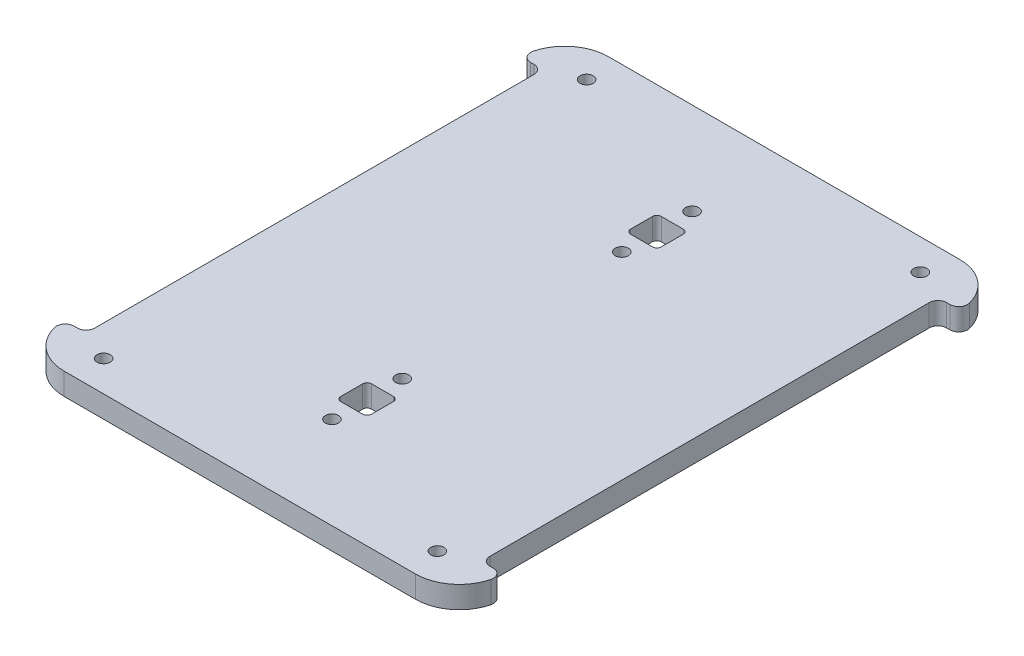
SolidWorks part; units mm, degrees
material "Acrílico (médio-alto impacto)"
ref_plane "Plano frontal" through (0, 0, 0) normal (0, 0, 1) x (1, 0, 0)
ref_plane "Plano superior" through (0, 0, 0) normal (0, 1, 0) x (1, 0, 0)
ref_plane "Plano direito" through (0, 0, 0) normal (1, 0, 0) x (0, 0, -1)
sketch "Esboço1" plane through (0, 0, 0) normal (0, 1, 0) x (1, 0, 0)
  line L0 (57.8257, 13.5994) -> (57.0797, 13.5994)
  line L1 (-29.9203, 127.5994) -> (50.0797, 127.5994)
  line L2 (57.8257, 117.5994) -> (57.0797, 117.5994)
  line L3 (-29.9203, 3.5994) -> (50.0797, 3.5994)
  line L4 (55.0797, 115.5994) -> (55.0797, 15.5994)
  line L5 (-37.6663, 117.5994) -> (-36.9203, 117.5994)
  line L6 (-37.6663, 13.5994) -> (-36.9203, 13.5994)
  line L7 (-34.9203, 115.5994) -> (-34.9203, 15.5994)
  arc A0 (59.7622, 120.0994) -> (50.0797, 127.5994) centre (50.0797, 117.5994) ccw
  arc A1 (50.0797, 3.5994) -> (59.7622, 11.0994) centre (50.0797, 13.5994) ccw
  arc A2 (-39.6028, 120.0994) -> (-29.9203, 127.5994) centre (-29.9203, 117.5994) cw
  arc A3 (-39.6028, 11.0994) -> (-29.9203, 3.5994) centre (-29.9203, 13.5994) ccw
  arc A4 (57.8257, 13.5994) -> (59.7622, 11.0994) centre (57.8257, 11.5994) cw
  arc A5 (55.0797, 15.5994) -> (57.0797, 13.5994) centre (57.0797, 15.5994) ccw
  arc A6 (57.8257, 117.5994) -> (59.7622, 120.0994) centre (57.8257, 119.5994) ccw
  arc A7 (55.0797, 115.5994) -> (57.0797, 117.5994) centre (57.0797, 115.5994) cw
  arc A8 (-36.9203, 117.5994) -> (-34.9203, 115.5994) centre (-36.9203, 115.5994) cw
  arc A9 (-37.6663, 117.5994) -> (-39.6028, 120.0994) centre (-37.6663, 119.5994) cw
  arc A10 (-36.9203, 13.5994) -> (-34.9203, 15.5994) centre (-36.9203, 15.5994) ccw
  arc A11 (-37.6663, 13.5994) -> (-39.6028, 11.0994) centre (-37.6663, 11.5994) ccw
  dimension "D1" = 10
  dimension "D2" = 2
extrude "Ressalto-extrusão1" add sketch "Esboço1" along normal blind 5
sketch "Esboço2" plane through (0, 5, 0) normal (0, 1, 0) x (1, 0, 0)
  line L0 (55.0797, 15.5994) -> (-49.7304, 15.5994) construction
  line L1 (-34.9203, 65.5994) -> (55.0797, 65.5994)
  line L2 (-34.9203, 115.5994) -> (-34.9203, 15.5994) construction
  line L3 (55.0797, 15.5994) -> (55.0797, 115.5994) construction
  line L4 (13.5797, 96.0994) -> (13.5797, 101.0994)
  line L5 (7.5797, 36.0994) -> (12.5797, 36.0994)
  line L6 (6.5797, 35.0994) -> (6.5797, 30.0994)
  line L7 (7.5797, 29.0994) -> (12.5797, 29.0994)
  line L8 (13.5797, 35.0994) -> (13.5797, 30.0994)
  line L9 (7.5797, 102.0994) -> (12.5797, 102.0994)
  line L10 (6.5797, 96.0994) -> (6.5797, 101.0994)
  line L11 (7.5797, 95.0994) -> (12.5797, 95.0994)
  circle A0 centre (10.0797, 24.5994) radius 1.5
  circle A1 centre (10.0797, 40.5994) radius 1.5
  circle A2 centre (10.0797, 90.5994) radius 1.5
  circle A3 centre (10.0797, 106.5994) radius 1.5
  arc A4 (12.5797, 36.0994) -> (13.5797, 35.0994) centre (12.5797, 35.0994) cw
  arc A5 (12.5797, 29.0994) -> (13.5797, 30.0994) centre (12.5797, 30.0994) ccw
  arc A6 (6.5797, 30.0994) -> (7.5797, 29.0994) centre (7.5797, 30.0994) ccw
  arc A7 (7.5797, 36.0994) -> (6.5797, 35.0994) centre (7.5797, 35.0994) ccw
  arc A8 (7.5797, 95.0994) -> (6.5797, 96.0994) centre (7.5797, 96.0994) cw
  arc A9 (6.5797, 101.0994) -> (7.5797, 102.0994) centre (7.5797, 101.0994) cw
  arc A10 (12.5797, 102.0994) -> (13.5797, 101.0994) centre (12.5797, 101.0994) cw
  arc A11 (12.5797, 95.0994) -> (13.5797, 96.0994) centre (12.5797, 96.0994) ccw
  dimension "D1" = 16
  dimension "D2" = 9
  dimension "D3" = 3
  dimension "D4" = 3
  dimension "D7" = 45
  dimension "D8" = 45
  dimension "D9" = 1
  dimension "D5" = 41.5
  dimension "D6" = 41.5
  dimension "D10" = 4.5
  dimension "D11" = 4.5
extrude "Corte-extrusão1" cut sketch "Esboço2" against normal blind 5 contours A1 | A0 | A2 | A3 | L6 A6 L7 A5 L8 A4 L5 A7 | L10 A9 L9 A10 L4 A11 L11 A8
sketch "Esboço3" plane through (0, 5, 0) normal (0, 1, 0) x (1, 0, 0)
  line L0 (-29.9203, 3.5994) -> (50.0797, 3.5994) construction
  line L1 (-34.9203, 115.5994) -> (-34.9203, 15.5994) construction
  line L2 (55.0797, 15.5994) -> (55.0797, 115.5994) construction
  line L3 (50.0797, 127.5994) -> (-29.9203, 127.5994) construction
  circle A0 centre (-27.9203, 10.5994) radius 1.5
  circle A1 centre (48.0797, 10.5994) radius 1.5
  circle A2 centre (-27.9203, 120.5994) radius 1.5
  circle A3 centre (48.0797, 120.5994) radius 1.5
  dimension "D1" = 7
  dimension "D2" = 7
  dimension "D3" = 7
  dimension "D4" = 7
  dimension "D5" = 7
  dimension "D6" = 7
  dimension "D7" = 7
  dimension "D8" = 7
extrude "Corte-extrusão2" cut sketch "Esboço3" against normal blind 10
